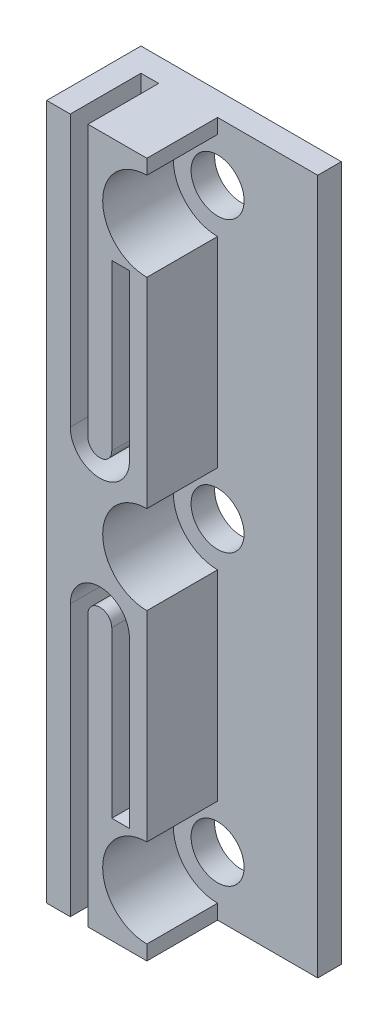
SolidWorks part; units mm, degrees
ref_plane "Plan de face" through (0, 0, 0) normal (0, 0, 1) x (1, 0, 0)
ref_plane "Plan de dessus" through (0, 0, 0) normal (0, 1, 0) x (1, 0, 0)
ref_plane "Plan de droite" through (0, 0, 0) normal (1, 0, 0) x (0, 0, -1)
sketch "Esquisse1" plane through (0, 0, 0) normal (0, 0, 1) x (1, 0, 0)
  line L1 (0, 0) -> (17, 0)
  line L2 (0, 0) -> (0, -59)
  line L3 (0, -59) -> (17, -59)
  line L4 (17, 0) -> (17, -59)
  dimension "D1" = 17
  dimension "D2" = 59
extrude "Boss.-Extru.1" add sketch "Esquisse1" along normal blind 2
sketch "Esquisse2" plane through (0, 0, 2) normal (0, 0, 1) x (1, 0, 0)
  line L0 (0, -59) -> (17, -59) construction
  line L1 (0, 0) -> (8.5, 0)
  line L2 (0, 0) -> (0, -59)
  line L3 (0, -59) -> (8.5, -59)
  line L4 (8.5, 0) -> (8.5, -59)
extrude "Boss.-Extru.2" add sketch "Esquisse2" along normal blind 6
sketch "Esquisse3" plane through (0, 0, 8) normal (0, 0, 1) x (1, 0, 0)
  line L0 (0, -59) -> (8.5, -59) construction
  line L1 (2, -59) -> (3.5, -59)
  line L2 (2, -59) -> (2, 0)
  line L3 (2, 0) -> (3.5, 0)
  line L4 (3.5, -59) -> (3.5, 0)
  line L5 (8.5, 0) -> (0, 0) construction
  line L6 (8.5, -59) -> (8.5, 0) construction
  line L7 (2, -23) -> (3.5, -23)
  line L8 (5.5199, -50) -> (7.0199, -50)
  line L9 (5.5199, -50) -> (5.5199, -9)
  line L10 (5.5199, -9) -> (7.0199, -9)
  line L11 (7.0199, -50) -> (7.0199, -9)
  line L13 (3.5, -23) -> (5.5199, -23)
  line L14 (5.5199, -23) -> (7.0908, -23)
  line L15 (2, -36) -> (3.5, -36)
  line L16 (3.5, -36) -> (5.5199, -36)
  line L17 (5.5199, -36) -> (7.0199, -36)
  arc A0 (2, -23) -> (7.0199, -23) centre (4.51, -23) ccw
  arc A1 (3.5, -23) -> (5.5199, -23) centre (4.51, -23) ccw
  arc A2 (3.5, -36) -> (5.5199, -36) centre (4.51, -36) cw
  arc A3 (2, -36) -> (7.0199, -36) centre (4.51, -36) cw
  point P14 (6.2699, -9)
  line M10 (0, -59) -> (8.5, -59)
  line M12 (8.5, 0) -> (0, 0)
  dimension "D1" = 1.5
  dimension "D2" = 5
  dimension "D3" = 1.5
  dimension "D4" = 9
  dimension "D5" = 9
  dimension "D6" = 13
  dimension "D7" = 14
  dimension "D8" = 14
extrude "Enlèv. mat.-Extru.1" cut sketch "Esquisse3" against normal blind 6 contours L15 L2 L4 M10 | A3 L15 L4 | A3 L4 A2 L9 | A3 L9 L17 | L17 L9 L8 L11 | L9 L14 L11 L10 | L2 L7 L4 M12 | L7 A0 L4 | A1 L4 A0 L9 | L9 A0 L14
sketch "Esquisse4" plane through (0, 0, 8) normal (0, 0, 1) x (1, 0, 0)
  line L2 (3.5, -59) -> (8.5, -59) construction
  line L3 (17, -59) -> (17, 0) construction
  line L4 (0, 0) -> (0, -59) construction
  line L5 (8.5, -59) -> (8.5, 0) construction
  line L6 (8.5, 0) -> (3.5, 0) construction
  circle A0 centre (8.5, -29.5) radius 2.25
  circle A1 centre (8.5, -54) radius 2.25
  circle A2 centre (8.5, -5) radius 2.25
  point P8 (6, -59)
  dimension "D1" = 4.5
  dimension "D2" = 4.5
  dimension "D3" = 4.5
  dimension "D4" = 29.5
  dimension "D5" = 17
  dimension "D6" = 5
  dimension "D7" = 8.5
  dimension "D8" = 5
extrude "Enlèv. mat.-Extru.4" cut sketch "Esquisse4" against normal blind 22
sketch "Esquisse6" plane through (0, 0, 8) normal (0, 0, 1) x (1, 0, 0)
  circle A0 centre (8.5, -29.5) radius 3.75
  circle A1 centre (8.5, -5) radius 3.75
  circle A2 centre (8.5, -54) radius 3.75
  dimension "D1" = 7.5
  dimension "D2" = 7.5
  dimension "D3" = 7.5
extrude "Enlèv. mat.-Extru.5" cut sketch "Esquisse6" against normal blind 6
